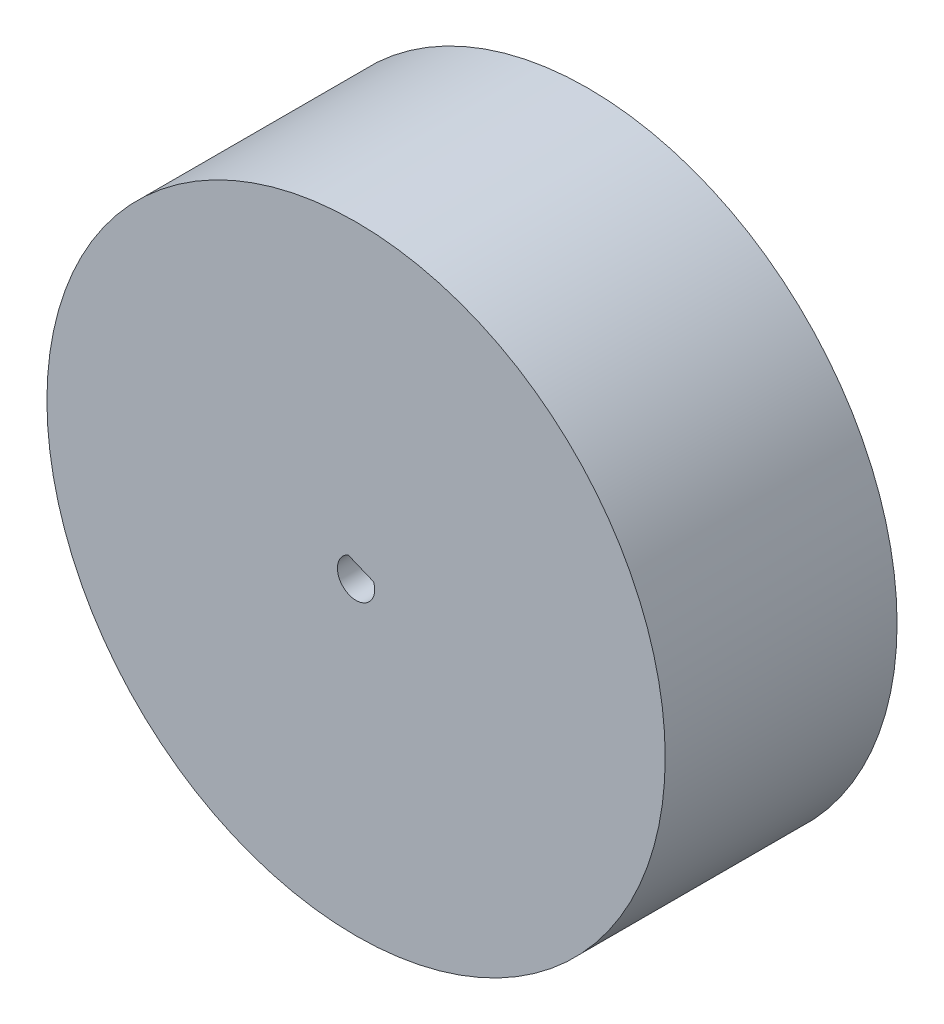
SolidWorks part; units mm, degrees
ref_plane "Front Plane" through (0, 0, 0) normal (0, 0, 1) x (1, 0, 0)
ref_plane "Top Plane" through (0, 0, 0) normal (0, 1, 0) x (1, 0, 0)
ref_plane "Right Plane" through (0, 0, 0) normal (1, 0, 0) x (0, 0, -1)
sketch "Sketch1" plane through (0, 0, 0) normal (0, 0, 1) x (1, 0, 0)
  line L0 (1.4158, 0.4955) -> (1.1504, 0.6055) construction
  line L1 (1.1504, 0.6055) -> (-0.3843, 1.2419) construction
  line L2 (-0.3843, 1.2419) -> (-0.6497, 1.352) construction
  line L3 (1.4158, 0.4955) -> (1.1504, 0.6055) construction
  line L4 (1.1504, 0.6055) -> (-0.3843, 1.2419) construction
  line L5 (-0.3843, 1.2419) -> (-0.6497, 1.352) construction
  line L6 (1.4396, 0.5181) -> (1.1618, 0.6333)
  line L7 (1.1618, 0.6333) -> (-0.3728, 1.2696)
  line L8 (-0.3728, 1.2696) -> (-0.6505, 1.3848)
  circle A0 centre (0, 0) radius 25.4
  arc A1 (1.3856, -0.5746) -> (1.4158, 0.4955) centre (0, 0) ccw construction
  arc A2 (-0.6497, 1.352) -> (-1.3856, 0.5746) centre (0, 0) ccw construction
  arc A3 (-1.3856, 0.5746) -> (1.3856, -0.5746) centre (0, 0) ccw construction
  arc A4 (1.3856, -0.5746) -> (1.4158, 0.4955) centre (0, 0) ccw construction
  arc A5 (-0.6497, 1.352) -> (-1.3856, 0.5746) centre (0, 0) ccw construction
  arc A6 (-1.3856, 0.5746) -> (1.3856, -0.5746) centre (0, 0) ccw construction
  arc A7 (-1.4133, 0.5861) -> (1.4133, -0.5861) centre (0, 0) ccw
  arc A8 (1.4133, -0.5861) -> (1.4396, 0.5181) centre (0, 0) ccw
  arc A9 (-0.6505, 1.3848) -> (-1.4133, 0.5861) centre (0, 0) ccw
  dimension "D1" = 50.8
  dimension "D2" = 0.03
extrude "Boss-Extrude1" add sketch "Sketch1" against normal mid plane 19.05
